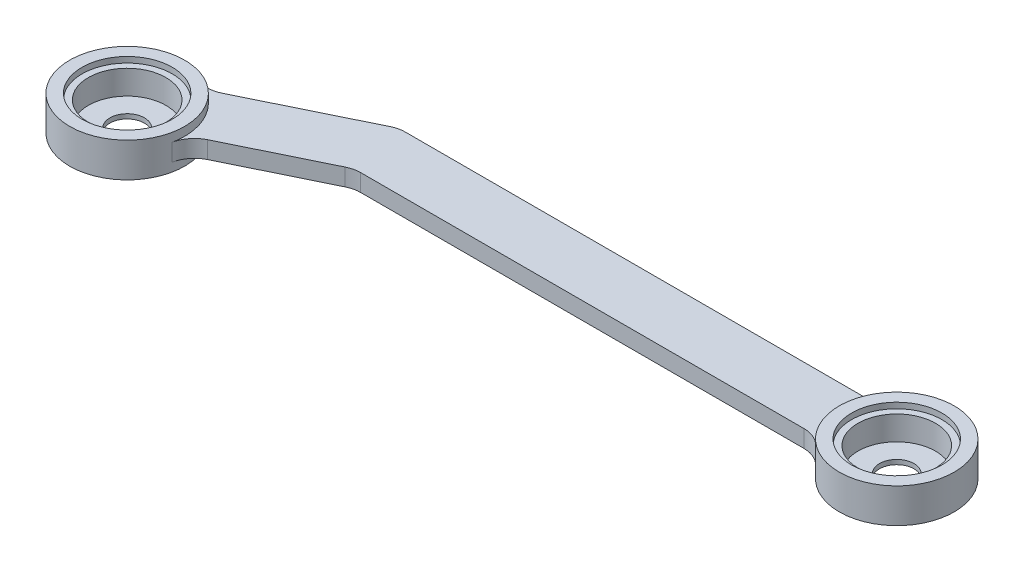
SolidWorks part; units mm, degrees
ref_plane "Front" through (0, 0, 0) normal (0, 0, 1) x (1, 0, 0)
ref_plane "Top" through (0, 0, 0) normal (0, 1, 0) x (1, 0, 0)
ref_plane "Right" through (0, 0, 0) normal (1, 0, 0) x (0, 0, -1)
sketch "Sketch1" plane through (0, 0, 0) normal (0, 1, 0) x (1, 0, 0)
  line L0 (-135.0672, 0) -> (21.4739, 0) construction
  line L1 (-11.1803, 5) -> (-90.4914, 5)
  line L2 (-11.1803, -5) -> (-88.2922, -5)
  line L3 (-90.4841, -5.506) -> (-109.084, -14.5779)
  line L4 (-92.6833, 4.494) -> (-112.2988, -5.0733)
  circle A0 centre (0, 0) radius 7.85
  arc A1 (-7.4536, -6.6667) -> (-7.4536, 6.6667) centre (0, 0) ccw
  circle A2 centre (-119.08, -14.86) radius 7.85
  arc A3 (-116.0205, -5.3395) -> (-109.084, -14.5779) centre (-119.08, -14.86) ccw
  arc A4 (-11.1803, -5) -> (-7.4536, -6.6667) centre (-11.1803, -10) cw
  arc A5 (-7.4536, 6.6667) -> (-11.1803, 5) centre (-11.1803, 10) cw
  arc A6 (-88.2922, -5) -> (-90.4841, -5.506) centre (-88.2922, -10) ccw
  arc A7 (-112.2988, -5.0733) -> (-116.0205, -5.3395) centre (-114.4907, -0.5793) cw
  arc A8 (-90.4914, 5) -> (-92.6833, 4.494) centre (-90.4914, 0) ccw
  circle A9 centre (-119.08, -14.86) radius 3
  circle A10 centre (0, 0) radius 3
  point P13 (-8.6603, -5)
  point P18 (-8.6603, 5)
  point P23 (-114.3263, -6.0621)
  dimension "D1" = 119.08
  dimension "D3" = 20
  dimension "D4" = 20
  dimension "D5" = 15.7
  dimension "D6" = 15.7
  dimension "D9" = 5
  dimension "D10" = 5
  dimension "D2" = 14.86
  dimension "D7" = 10
  dimension "D8" = 10
extrude "Boss-Extrude1" add sketch "Sketch1" along normal mid plane 6 contours A2 A9 | L0 L4 A7 A3 L3 A6 L2 A4 A1 A0 A2 | L4 L0 A0 A1 A5 L1 A8 | L0 A0 A10 | A0 L0 A10
sketch "Sketch2" plane through (0, 3, 0) normal (0, 1, 0) x (1, 0, 0)
  circle A0 centre (-119.08, -14.86) radius 10
  circle A1 centre (0, 0) radius 10
sketch "Sketch3" plane through (0, -3, 0) normal (0, -1, 0) x (1, 0, 0)
  line L0 (-90.4841, 5.506) -> (-109.084, 14.5779) construction
  line L1 (-90.4841, 5.506) -> (-106.5722, 13.3528)
  line L2 (-106.5722, 13.3528) -> (-109.084, 14.5779)
  line L3 (-109.2802, 16.8512) -> (-109.738, 15.3287)
  line L4 (-109.738, 15.3287) -> (-109.084, 14.5779)
  line L5 (-106.5722, 13.3528) -> (-109.084, 14.5779)
  arc A0 (-109.084, 14.5779) -> (-116.0205, 5.3395) centre (-119.08, 14.86) ccw construction
  arc A1 (-109.2802, 16.8512) -> (-116.0205, 5.3395) centre (-119.08, 14.86) ccw
  arc A2 (-109.2802, 16.8512) -> (-106.5722, 13.3528) centre (-104.3804, 17.8468) ccw
  line M10 (-90.4841, 5.506) -> (-109.084, 14.5779)
  arc M11 (-109.084, 14.5779) -> (-116.0205, 5.3395) centre (-119.08, 14.86) ccw
  dimension "D1" = 5
extrude "Boss-Extrude2" add sketch "Sketch3" against normal blind 6 contours A2 M11 M10 | L3 L4 M11
sketch "Sketch4" plane through (0, 3, 0) normal (0, 1, 0) x (1, 0, 0)
  line L0 (-11.1803, 5) -> (-90.4914, 5) construction
  line L1 (-11.1803, -5) -> (-88.2922, -5) construction
  line L2 (-90.4841, -5.506) -> (-109.084, -14.5779) construction
  line L3 (-92.6833, 4.494) -> (-112.2988, -5.0733) construction
  line L4 (-11.1803, 5) -> (-90.4914, 5)
  line L5 (-11.1803, -5) -> (-88.2922, -5)
  line L6 (-90.4841, -5.506) -> (-109.084, -14.5779)
  line L7 (-92.6833, 4.494) -> (-112.2988, -5.0733)
  arc A0 (-7.4536, -6.6667) -> (-7.4536, 6.6667) centre (0, 0) ccw construction
  arc A1 (-11.1803, 5) -> (-7.4536, 6.6667) centre (-11.1803, 10) ccw construction
  arc A2 (-7.4536, -6.6667) -> (-11.1803, -5) centre (-11.1803, -10) ccw construction
  arc A3 (-90.4914, 5) -> (-92.6833, 4.494) centre (-90.4914, 0) ccw construction
  arc A4 (-88.2922, -5) -> (-90.4841, -5.506) centre (-88.2922, -10) ccw construction
  arc A5 (-106.5722, -13.3528) -> (-109.2802, -16.8512) centre (-104.3804, -17.8468) ccw construction
  arc A6 (-116.0205, -5.3395) -> (-112.2988, -5.0733) centre (-114.4907, -0.5793) ccw construction
  arc A7 (-7.4536, -6.6667) -> (-7.4536, 6.6667) centre (0, 0) ccw
  arc A8 (-11.1803, 5) -> (-7.4536, 6.6667) centre (-11.1803, 10) ccw
  arc A9 (-7.4536, -6.6667) -> (-11.1803, -5) centre (-11.1803, -10) ccw
  arc A10 (-90.4914, 5) -> (-92.6833, 4.494) centre (-90.4914, 0) ccw
  arc A11 (-88.2922, -5) -> (-90.4841, -5.506) centre (-88.2922, -10) ccw
  arc A12 (-106.5722, -13.3528) -> (-109.2802, -16.8512) centre (-104.3804, -17.8468) ccw
  arc A13 (-116.0205, -5.3395) -> (-112.2988, -5.0733) centre (-114.4907, -0.5793) ccw
  circle A14 centre (0, 0) radius 10 construction
  circle A15 centre (-119.08, -14.86) radius 10 construction
  circle A16 centre (0, 0) radius 10
  circle A17 centre (-119.08, -14.86) radius 10
  arc M2 (-109.2802, -16.8512) -> (-106.5722, -13.3528) centre (-104.3804, -17.8468) cw
  line M3 (-106.5722, -13.3528) -> (-90.4841, -5.506)
  arc M4 (-90.4841, -5.506) -> (-88.2922, -5) centre (-88.2922, -10) cw
  line M5 (-88.2922, -5) -> (-11.1803, -5)
  arc M6 (-11.1803, -5) -> (-7.4536, -6.6667) centre (-11.1803, -10) cw
  arc M8 (-7.4536, 6.6667) -> (-11.1803, 5) centre (-11.1803, 10) cw
  line M9 (-11.1803, 5) -> (-90.4914, 5)
  arc M10 (-90.4914, 5) -> (-92.6833, 4.494) centre (-90.4914, 0) ccw
  line M11 (-92.6833, 4.494) -> (-112.2988, -5.0733)
  arc M12 (-112.2988, -5.0733) -> (-116.0205, -5.3395) centre (-114.4907, -0.5793) cw
extrude "Cut-Extrude1" cut sketch "Sketch4" against normal blind 1.5 contours A17 L6 A16 M3 M4 M5 M6 M8 M9 M10 M11 M12 | A17 L6 M2
sketch "Sketch5" plane through (0, -3, 0) normal (0, -1, 0) x (1, 0, 0)
  line L0 (-11.1803, -5) -> (-90.4914, -5) construction
  line L1 (-11.1803, 5) -> (-88.2922, 5) construction
  line L2 (-92.6833, -4.494) -> (-112.2988, 5.0733) construction
  line L3 (-90.4841, 5.506) -> (-109.084, 14.5779) construction
  line L4 (-11.1803, -5) -> (-90.4914, -5)
  line L5 (-11.1803, 5) -> (-88.2922, 5)
  line L6 (-92.6833, -4.494) -> (-112.2988, 5.0733)
  line L7 (-90.4841, 5.506) -> (-109.084, 14.5779)
  arc A0 (-7.4536, -6.6667) -> (-11.1803, -5) centre (-11.1803, -10) ccw construction
  arc A1 (-11.1803, 5) -> (-7.4536, 6.6667) centre (-11.1803, 10) ccw construction
  circle A2 centre (0, 0) radius 10 construction
  arc A3 (-92.6833, -4.494) -> (-90.4914, -5) centre (-90.4914, 0) ccw construction
  arc A4 (-90.4841, 5.506) -> (-88.2922, 5) centre (-88.2922, 10) ccw construction
  arc A5 (-112.2988, 5.0733) -> (-116.0205, 5.3395) centre (-114.4907, 0.5793) ccw construction
  circle A6 centre (-119.08, 14.86) radius 10 construction
  arc A7 (-109.084, 14.5779) -> (-116.0205, 5.3395) centre (-119.08, 14.86) ccw construction
  arc A8 (-109.2802, 16.8512) -> (-106.5722, 13.3528) centre (-104.3804, 17.8468) ccw construction
  arc A9 (-7.4536, -6.6667) -> (-11.1803, -5) centre (-11.1803, -10) ccw
  arc A10 (-11.1803, 5) -> (-7.4536, 6.6667) centre (-11.1803, 10) ccw
  circle A11 centre (0, 0) radius 10
  arc A12 (-92.6833, -4.494) -> (-90.4914, -5) centre (-90.4914, 0) ccw
  arc A13 (-90.4841, 5.506) -> (-88.2922, 5) centre (-88.2922, 10) ccw
  arc A14 (-112.2988, 5.0733) -> (-116.0205, 5.3395) centre (-114.4907, 0.5793) ccw
  circle A15 centre (-119.08, 14.86) radius 10
  arc A16 (-109.084, 14.5779) -> (-116.0205, 5.3395) centre (-119.08, 14.86) ccw
  arc A17 (-109.2802, 16.8512) -> (-106.5722, 13.3528) centre (-104.3804, 17.8468) ccw
  line M3 (-90.4841, 5.506) -> (-106.5722, 13.3528)
  arc M4 (-106.5722, 13.3528) -> (-109.2802, 16.8512) centre (-104.3804, 17.8468) cw
  arc M6 (-116.0205, 5.3395) -> (-112.2988, 5.0733) centre (-114.4907, 0.5793) cw
  line M7 (-112.2988, 5.0733) -> (-92.6833, -4.494)
  arc M8 (-92.6833, -4.494) -> (-90.4914, -5) centre (-90.4914, 0) ccw
  line M9 (-90.4914, -5) -> (-11.1803, -5)
  arc M10 (-11.1803, -5) -> (-7.4536, -6.6667) centre (-11.1803, -10) cw
  arc M12 (-7.4536, 6.6667) -> (-11.1803, 5) centre (-11.1803, 10) cw
  line M13 (-11.1803, 5) -> (-88.2922, 5)
  arc M14 (-88.2922, 5) -> (-90.4841, 5.506) centre (-88.2922, 10) cw
extrude "Cut-Extrude3" cut sketch "Sketch5" against normal blind 1.5 contours A15 L7 M4 | A15 A11 L7 M6 M7 M8 M9 M10 M12 M13 M14 M3
sketch "Sketch6" plane through (0, 3, 0) normal (0, 1, 0) x (1, 0, 0)
  circle A0 centre (-119.08, -14.86) radius 7.85
  circle A1 centre (0, 0) radius 7.85
extrude "Cut-Extrude4" cut sketch "Sketch6" against normal blind 1
sketch "Sketch7" plane through (0, 2, 0) normal (0, 1, 0) x (1, 0, 0)
  circle A0 centre (-119.08, -14.86) radius 6.75
  circle A1 centre (0, 0) radius 6.75
extrude "Cut-Extrude5" cut sketch "Sketch7" against normal blind 4.2
